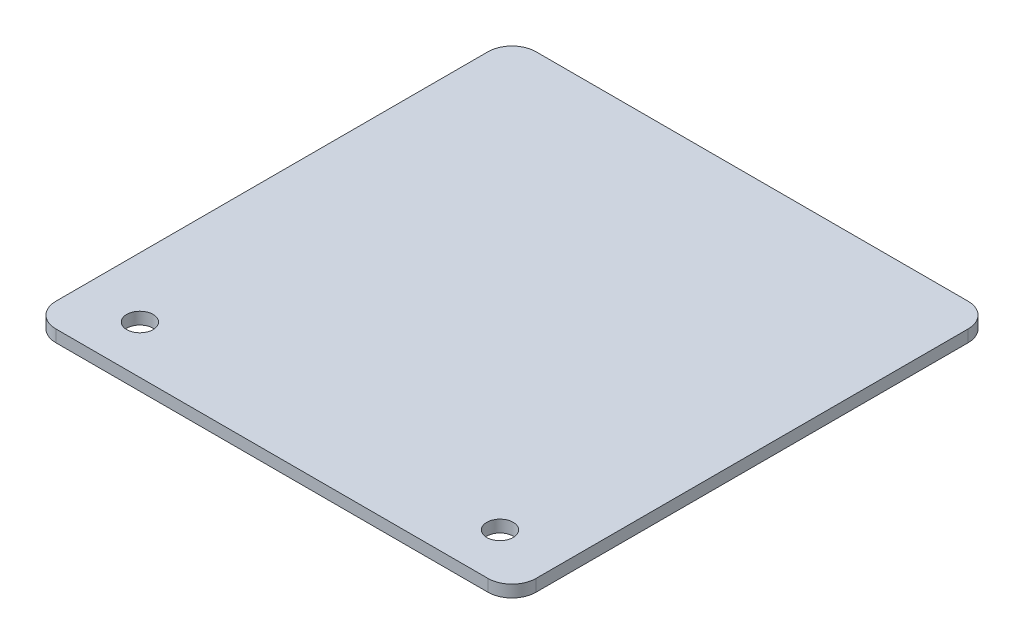
SolidWorks part; units mm, degrees
ref_plane "Front Plane" through (0, 0, 0) normal (0, 0, 1) x (1, 0, 0)
ref_plane "Top Plane" through (0, 0, 0) normal (0, 1, 0) x (1, 0, 0)
ref_plane "Right Plane" through (0, 0, 0) normal (1, 0, 0) x (0, 0, -1)
sketch "Sketch1" plane through (0, 0, 0) normal (0, 1, 0) x (1, 0, 0)
  line L1 (-50, -50) -> (50, -50)
  line L2 (-50, -50) -> (-50, 50)
  line L3 (-50, 50) -> (50, 50)
  line L4 (50, -50) -> (50, 50)
  line L5 (-50, -50) -> (50, 50) construction
  line L6 (-50, 50) -> (50, -50) construction
  point P0 (0, 0)
  dimension "D1" = 100
  dimension "D2" = 100
extrude "Boss-Extrude1" add sketch "Sketch1" along normal blind 2.5
hole_wizard "M5 Clearance Hole1" positions "Sketch5" profile "Sketch6" hole size "M5" standard "ANSI Metric"
sketch "Sketch5" plane through (0, 2.5, 0) normal (0, 1, 0) x (1, 0, 0)
  line L0 (-37.5, -40) -> (37.5, -40) construction
  line L2 (-50, -50) -> (50, -50) construction
  point P0 (-37.5, -40)
  point P2 (37.5, -40)
  point P7 (0, -40)
  dimension "D1" = 10
  dimension "D2" = 75
sketch "Sketch6" plane through (-37.5, 2.5, 40) normal (1, 0, 0) x (0, 0, 1)
  line L0 (0, 0) -> (0, 13.6524)
  line L1 (0, 13.6524) -> (2.75, 12)
  line L2 (2.75, 12) -> (2.75, 0)
  line L5 (2.75, 0) -> (0, 0)
  line L10 (0, 13.6524) -> (-2.75, 12) construction
  line L11 (0, -6.35) -> (0, 107.95) construction
  dimension "Hole Dia." = 5.5
  dimension "Hole Depth" = 12
  dimension "Drill Angle" = 118
fillet "Fillet1" radius 5 4 edges at (50, 1.25, -50) (-50, 1.25, 50) (50, 1.25, 50) (-50, 1.25, -50)
